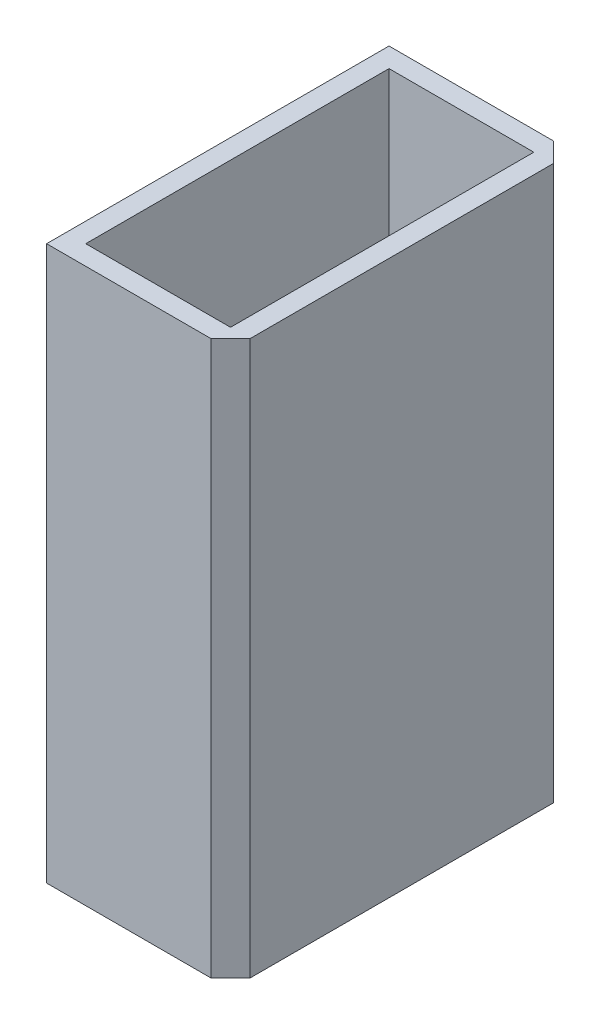
SolidWorks part; units mm, degrees
ref_plane "Front Plane" through (0, 0, 0) normal (0, 0, 1) x (1, 0, 0)
ref_plane "Top Plane" through (0, 0, 0) normal (0, 1, 0) x (1, 0, 0)
ref_plane "Right Plane" through (0, 0, 0) normal (1, 0, 0) x (0, 0, -1)
sketch "Sketch1" plane through (0, 0, 0) normal (0, 1, 0) x (1, 0, 0)
  line L0 (-2.54, -2.54) -> (21.336, -2.54)
  line L1 (0, 0) -> (18.796, 0)
  line L2 (0, 0) -> (0, 39.37)
  line L3 (0, 39.37) -> (18.796, 39.37)
  line L4 (18.796, 0) -> (18.796, 39.37)
  line L5 (21.336, -2.54) -> (21.336, 41.91)
  line L6 (-2.54, 41.91) -> (21.336, 41.91)
  line L7 (-2.54, -2.54) -> (-2.54, 41.91)
  dimension "D1" = 39.37
  dimension "D2" = 18.796
  dimension "D3" = 2.54
extrude "Boss-Extrude1" add sketch "Sketch1" along normal blind 69.342
sketch "Sketch2" plane through (0, 0, 0) normal (0, -1, 0) x (1, 0, 0)
  line L1 (21.336, -41.91) -> (-2.54, -41.91)
  line L2 (21.336, -41.91) -> (21.336, 2.54)
  line L3 (21.336, 2.54) -> (-2.54, 2.54)
  line L4 (-2.54, -41.91) -> (-2.54, 2.54)
extrude "Boss-Extrude2" add sketch "Sketch2" along normal blind 2.54
chamfer "Chamfer1" distance 2.54 angle 45 2 edges at (21.336, 33.401, -41.91) (21.336, 33.401, 2.54)
